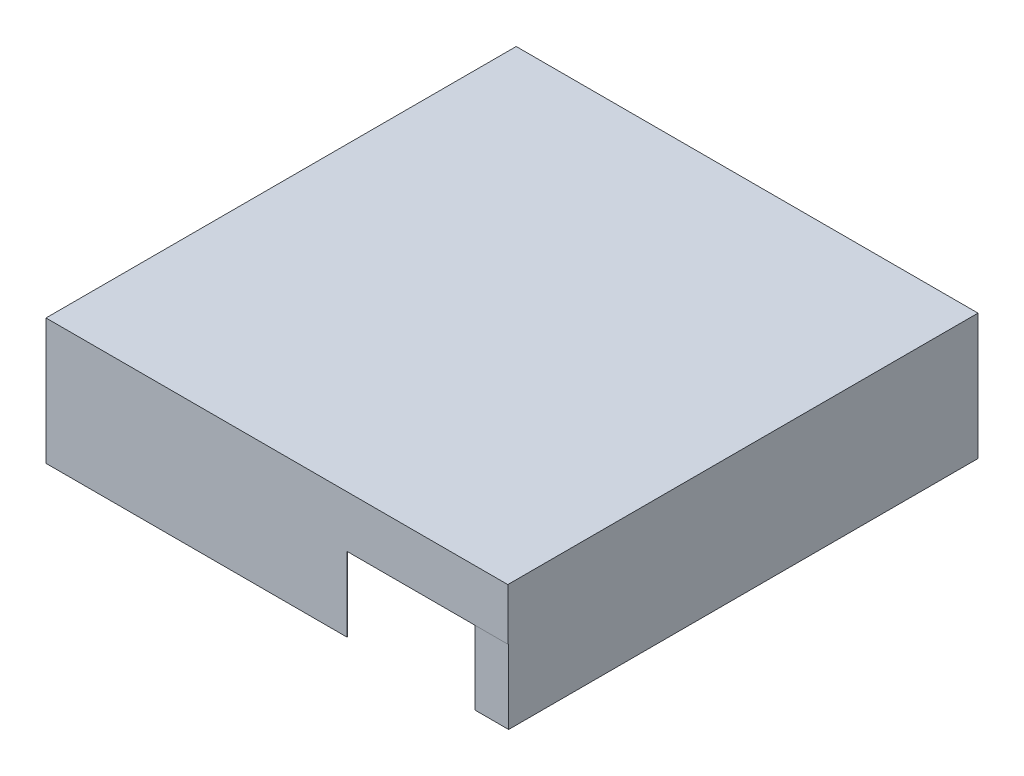
SolidWorks part; units mm, degrees
ref_plane "Front Plane" through (0, 0, 0) normal (0, 0, 1) x (1, 0, 0)
ref_plane "Top Plane" through (0, 0, 0) normal (0, 1, 0) x (1, 0, 0)
ref_plane "Right Plane" through (0, 0, 0) normal (1, 0, 0) x (0, 0, -1)
sketch "Sketch1" plane through (0, 0, 0) normal (0, 0, 1) x (-1, 0, 0)
  line L1 (-14.0585, 9) -> (14.0585, 9)
  line L3 (-14.0585, -9) -> (14.0585, -9)
  line L5 (-14.693, 7.9219) -> (14.693, -7.9219) construction
  line L6 (-14.693, -7.9219) -> (14.693, 7.9219) construction
  circle A0 centre (0, 0) radius 29.6925
  circle A1 centre (0, 0) radius 22.6925
  circle A2 centre (0, 0) radius 16.6925
  circle A3 centre (0, 0) radius 19.6925
  point P5 (0, 16.6925)
  point P7 (16.6925, 0)
  point P9 (0, -16.6925)
  point P11 (-16.6925, 0)
  dimension "D1" = 6
  dimension "D2" = 45.3851
  dimension "D3" = 3
  dimension "D4" = 7
  dimension "D5" = 33.3851
  dimension "D7" = 59.3851
  dimension "D6" = 18
sketch "Sketch4" plane through (0, 0, 0) normal (0, 0, 1) x (-1, 0, 0)
  line L1 (-14.0585, 10.3647) -> (14.0585, 10.3647)
  line L3 (-14.0585, -7.6353) -> (14.0585, -7.6353)
  line L5 (-14.693, 7.9219) -> (14.693, -7.9219) construction
  line L6 (-14.693, -7.9219) -> (14.693, 7.9219) construction
  circle A0 centre (0, 0) radius 29.6925
  circle A1 centre (0, 0) radius 22.6925
  circle A3 centre (0, 0) radius 19.6925
  point P22 (0, 19.6925)
  point P24 (0, -19.6925)
  point P26 (19.6925, 0)
  point P28 (-19.6925, 0)
  dimension "D2" = 45.3851
  dimension "D3" = 3
  dimension "D4" = 7
  dimension "D6" = 18
hole_wizard "CSK for M3 Flat Head Machine Screw2" positions "Sketch7" profile "Sketch8" countersink size "M3" standard "ANSI Metric"
sketch "Sketch7" plane through (0, 0, 5) normal (0, 0, 1) x (1, 0, 0)
  point P0 (0, 19.6925)
  point P3 (0, -19.6925)
  point P6 (19.6925, 0)
  point P9 (-19.6925, 0)
sketch "Sketch8" plane through (0, 19.6925, 5) normal (1, 0, 0) x (0, -1, 0)
  line L0 (0, 0) -> (0, 13.0215)
  line L1 (0, 13.0215) -> (1.7, 12)
  line L2 (1.7, 12) -> (1.7, 1.95)
  line L3 (1.7, 1.95) -> (3.65, 0)
  line L5 (3.65, 0) -> (0, 0)
  line L6 (-1.7, 1.95) -> (-3.65, 0) construction
  line L10 (0, 13.0215) -> (-1.7, 12) construction
  line L11 (0, -6.35) -> (0, 107.95) construction
  dimension "Hole Dia." = 3.4
  dimension "Hole Depth" = 12
  dimension "Near C'Sink Dia." = 7.3
  dimension "Near C'Sink Angle" = 90
  dimension "Drill Angle" = 118
sketch "Sketch9" plane through (0, 0, 0) normal (0, 1, 0) x (1, 0, 0)
  line L1 (-13.75, 0) -> (13.75, 0)
  line L7 (14.693, 0) -> (-14.693, 0) construction
  line L8 (-13.75, 28) -> (13.75, 0) construction
  line L9 (-13.75, 0) -> (13.75, 28) construction
  line L10 (13.75, 0) -> (13.75, 28)
  line L11 (-13.75, 28) -> (13.75, 28)
  line L12 (-13.75, 0) -> (-13.75, 28)
  point P0 (0, 14)
  point P18 (0, 8.5)
  dimension "D1" = 27.5
  dimension "D2" = 28
  dimension "D3" = 28
extrude "Boss-Extrude2" add sketch "Sketch9" along normal mid plane 15
sketch "Sketch10" plane through (0, 0, 0) normal (0, 1, 0) x (1, 0, 0)
  line L0 (-13.75, 28) -> (13.75, 28)
  line L1 (-13.75, 28) -> (-13.75, 0.1022)
  line L2 (13.75, 28) -> (13.75, 0.1022)
  line L3 (-13.75, 0.1022) -> (13.75, 0.1022)
  line L4 (-13.75, 28) -> (13.75, 0.1022) construction
  line L5 (-13.75, 0.1022) -> (13.75, 28) construction
  line L6 (-11.75, 0.05) -> (11.75, 0.05)
  line L7 (-11.75, 0.05) -> (-11.75, 25.5)
  line L8 (11.75, 0.05) -> (11.75, 25.5)
  line L9 (-11.75, 25.5) -> (11.75, 25.5)
  point P0 (0, 0.05)
  dimension "D1" = 25.45
  dimension "D2" = 23.5
  dimension "D3" = 2.5
sketch "Sketch11" plane through (0, 0, 5) normal (0, 0, 1) x (1, 0, 0)
  line L0 (13.75, -5.2927) -> (13.75, 4.425)
  line L5 (13.75, -5.2927) -> (4.1647, -5.2927)
  line L6 (13.75, 4.425) -> (4.1647, 4.425)
  line L7 (4.1647, -5.2927) -> (4.1647, 4.425)
  line L8 (13.75, 7.5) -> (13.75, -7.5) construction
extrude "Cut-Extrude1" cut sketch "Sketch10" against normal mid plane 12.2 contours L8 L9 L7 L6
sketch "Sketch12" plane through (0, 0, -28) normal (0, 0, 1) x (1, 0, 0)
  line L1 (-9.25, 6.15) -> (9.25, 6.15)
  line L2 (-9.25, 6.15) -> (-9.25, -6.15)
  line L3 (-9.25, -6.15) -> (9.25, -6.15)
  line L4 (9.25, 6.15) -> (9.25, -6.15)
  line L5 (-9.25, 6.15) -> (9.25, -6.15) construction
  line L6 (-9.25, -6.15) -> (9.25, 6.15) construction
  point P0 (0, 0)
  dimension "D1" = 12.3
  dimension "18.5" = 18.5
extrude "Cut-Extrude2" cut sketch "Sketch12" along normal blind 3 contours L3 L4 L1 L2
extrude "Cut-Extrude3" cut sketch "Sketch11" against normal up to surface (5.05 mm away) contours L6 L7 L5 L0 up to face at (0, 0, -0.05)
split "Split1" trim tools "Top Plane" bodies to split 110 resulting bodies 111 112
split "Split2" bodies to split 111 112
delete or keep bodies "Body-Delete/Keep 2" type delete bodies bodies 112
